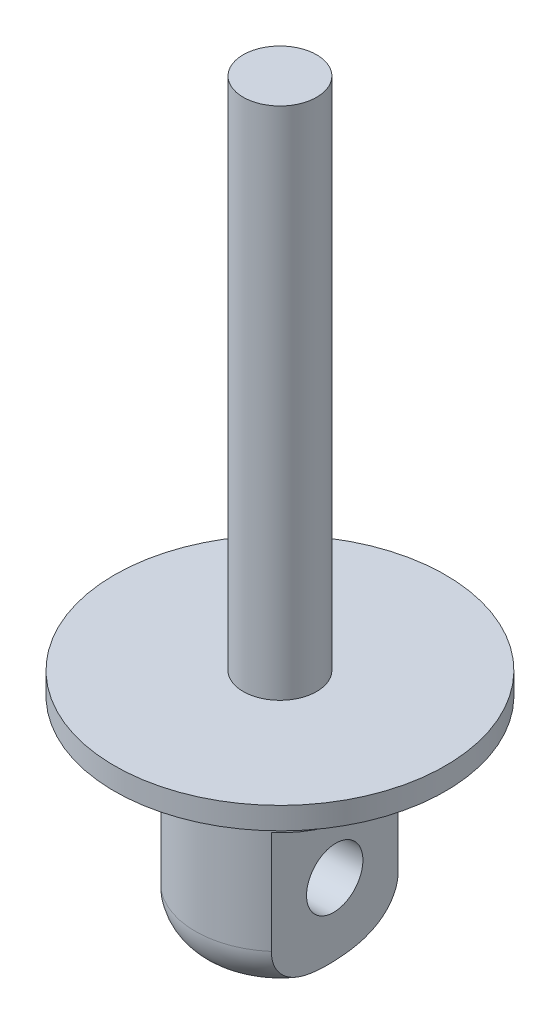
SolidWorks part; units mm, degrees
ref_plane "Front Plane" through (0, 0, 0) normal (0, 0, 1) x (1, 0, 0)
ref_plane "Top Plane" through (0, 0, 0) normal (0, 1, 0) x (1, 0, 0)
ref_plane "Right Plane" through (0, 0, 0) normal (1, 0, 0) x (0, 0, -1)
sketch "Sketch1" plane through (0, 0, 0) normal (0, 0, 1) x (1, 0, 0)
  line L0 (0, 0) -> (11.5, 0)
  line L1 (11.5, 0) -> (11.5, 28)
  line L2 (11.5, 28) -> (22.5, 28)
  line L3 (22.5, 28) -> (22.5, 31)
  line L4 (22.5, 31) -> (5, 31)
  line L5 (5, 31) -> (5, 101)
  line L6 (5, 101) -> (0, 101)
  line L7 (0, 101) -> (0, 0)
  dimension "D1" = 5
  dimension "D2" = 101
  dimension "D3" = 3
  dimension "D4" = 28
  dimension "D5" = 11.5
  dimension "D6" = 22.5
revolve "Revolve1" add sketch "Sketch1" angle 360 about L7
fillet "Fillet1" radius 6 1 edges at (-11.5, 0, 0)
sketch "Sketch2" plane through (0, 0, 0) normal (0, -1, 0) x (1, 0, 0)
  line L0 (0, 0) -> (0.3646, 17.8342) construction
  line L1 (15.765, 15.943) -> (14.4103, -17.1773)
  line L2 (-15.1003, 16.574) -> (-7.1643, 16.574)
  line L3 (-15.1003, 16.574) -> (-15.1003, -16.574)
  line L4 (-15.1003, -16.574) -> (-7.1643, -16.574)
  line L5 (-7.1643, 16.574) -> (-7.1643, -16.574)
  line L6 (-15.1003, 16.574) -> (-7.1643, -16.574) construction
  line L7 (-15.1003, -16.574) -> (-7.1643, 16.574) construction
  line L8 (15.765, 15.943) -> (6.481, -16.8529) construction
  line L9 (14.4103, -17.1773) -> (7.8357, 16.2673) construction
  line L10 (15.765, 15.943) -> (7.8357, 16.2673)
  line L11 (7.8357, 16.2673) -> (6.481, -16.8529)
  line L12 (14.4103, -17.1773) -> (6.481, -16.8529)
  point P3 (-11.1323, 0)
  point P12 (11.123, -0.455)
  point P13 (0, 0)
  dimension "D1" = 15
extrude "Cut-Extrude1" cut sketch "Sketch2" against normal blind 20
sketch "Sketch3" plane through (7.1583, 0, -0.2928) normal (0.9992, 0, -0.0409) x (-0.0409, 0, -0.9992)
  line L0 (-5.5, 0) -> (5.5, 0) construction
  circle A0 centre (0, 10) radius 4
  dimension "D1" = 8
  dimension "D2" = 10
extrude "Cut-Extrude2" cut sketch "Sketch3" against normal through all
